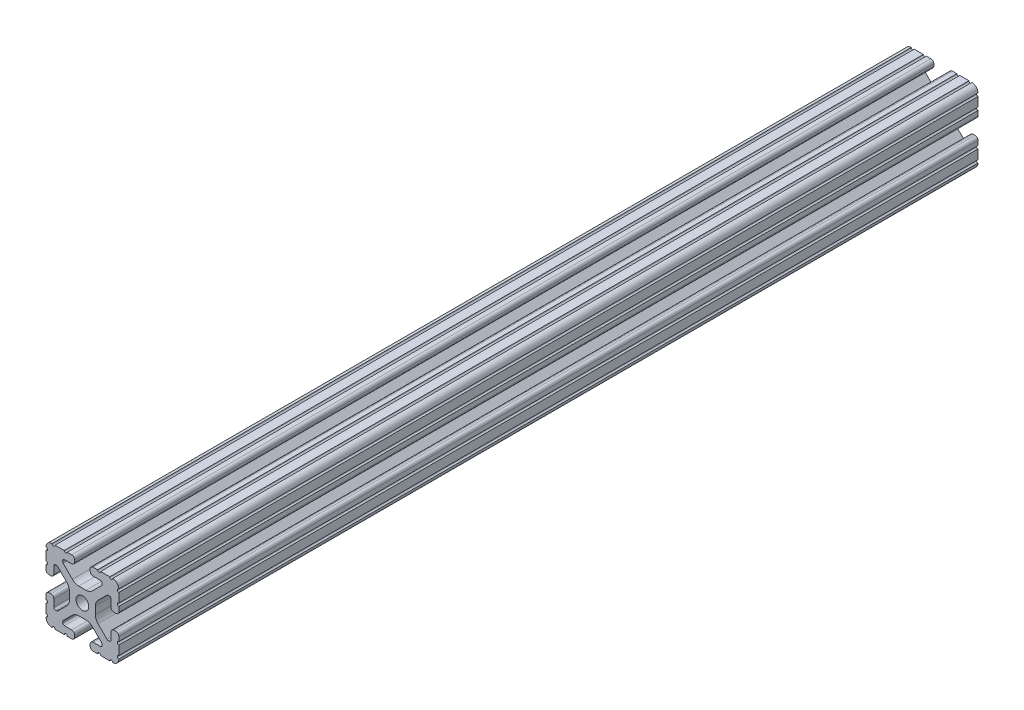
SolidWorks part; units mm, degrees
material "6061 Alloy"
ref_plane "Front Plane" through (0, 0, 0) normal (0, 0, 1) x (1, 0, 0)
ref_plane "Top Plane" through (0, 0, 0) normal (0, 1, 0) x (1, 0, 0)
ref_plane "Right Plane" through (0, 0, 0) normal (1, 0, 0) x (0, 0, -1)
sketch "Sketch1" plane through (0, 0, 0) normal (0, 0, 1) x (1, 0, 0)
  line L0 (0, 25.6181) -> (0, -24.623) construction
  line L1 (-20.8943, 0) -> (20.4607, 0) construction
  line L2 (-10.0229, 12.9148) -> (-5.2522, 8.144)
  line L3 (-10.287, 14.0843) -> (-10.287, 13.5524)
  line L4 (-5.6176, 14.986) -> (-9.3853, 14.986)
  line L5 (-4.064, 17.4964) -> (-4.064, 16.5396)
  line L6 (-7.9742, 19.05) -> (-5.6176, 19.05)
  line L7 (-14.3277, 19.05) -> (-9.4982, 19.05)
  line L8 (-19.05, 9.4961) -> (-19.05, 14.3277)
  line L9 (-19.05, 5.6176) -> (-19.05, 7.9763)
  line L10 (-16.5396, 4.064) -> (-17.4964, 4.064)
  line L11 (-14.986, 9.3853) -> (-14.986, 5.6176)
  line L12 (-13.516, 10.287) -> (-14.0843, 10.287)
  line L13 (-8.1476, 5.2921) -> (-12.8784, 10.0229)
  line L14 (-6.7564, -1.9335) -> (-6.7564, 1.9335)
  line L15 (-12.8784, -10.0229) -> (-8.1476, -5.2921)
  line L16 (-14.0843, -10.287) -> (-13.516, -10.287)
  line L17 (-14.986, -5.6176) -> (-14.986, -9.3853)
  line L18 (-17.4964, -4.064) -> (-16.5396, -4.064)
  line L19 (-19.05, -7.9763) -> (-19.05, -5.6176)
  line L20 (-19.05, -14.3277) -> (-19.05, -9.4961)
  line L21 (-9.4961, -19.05) -> (-14.3277, -19.05)
  line L22 (-5.6176, -19.05) -> (-7.9763, -19.05)
  line L23 (-4.064, -17.4964) -> (-4.064, -16.5396)
  line L24 (10.0229, -12.9148) -> (5.2522, -8.144)
  line L25 (10.287, -14.0843) -> (10.287, -13.5524)
  line L26 (5.6176, -14.986) -> (9.3853, -14.986)
  line L28 (-1.9022, 6.7564) -> (1.9022, 6.7564)
  line L29 (-1.9022, -6.7564) -> (1.9022, -6.7564)
  line L31 (-5.6176, -14.986) -> (-9.3853, -14.986)
  line L32 (-10.287, -14.0843) -> (-10.287, -13.5524)
  line L33 (-10.0229, -12.9148) -> (-5.2522, -8.144)
  line L66 (4.064, -16.5396) -> (4.064, -17.4964)
  line L67 (5.6176, -19.05) -> (7.9763, -19.05)
  line L68 (9.4961, -19.05) -> (14.3277, -19.05)
  line L69 (19.05, -14.3277) -> (19.05, -9.4961)
  line L70 (19.05, -7.9763) -> (19.05, -5.6176)
  line L71 (17.4964, -4.064) -> (16.5396, -4.064)
  line L72 (14.986, -5.6176) -> (14.986, -9.3853)
  line L73 (14.0843, -10.287) -> (13.516, -10.287)
  line L74 (12.8784, -10.0229) -> (8.1476, -5.2921)
  line L75 (6.7564, -1.9335) -> (6.7564, 1.9335)
  line L76 (8.1476, 5.2921) -> (12.8784, 10.0229)
  line L77 (13.516, 10.287) -> (14.0843, 10.287)
  line L78 (14.986, 9.3853) -> (14.986, 5.6176)
  line L79 (16.5396, 4.064) -> (17.4964, 4.064)
  line L80 (19.05, 5.6176) -> (19.05, 7.9763)
  line L81 (19.05, 9.4961) -> (19.05, 14.3277)
  line L82 (14.3277, 19.05) -> (9.4982, 19.05)
  line L83 (7.9742, 19.05) -> (5.6176, 19.05)
  line L84 (4.064, 17.4964) -> (4.064, 16.5396)
  line L85 (5.6176, 14.986) -> (9.3853, 14.986)
  line L86 (10.287, 14.0843) -> (10.287, 13.5524)
  line L87 (10.0229, 12.9148) -> (5.2522, 8.144)
  arc A0 (-10.0229, 12.9148) -> (-10.287, 13.5524) centre (-9.3853, 13.5524) cw
  circle A1 centre (0, 0) radius 3.3274
  arc A2 (-10.287, 14.0843) -> (-9.3853, 14.986) centre (-9.3853, 14.0843) cw
  arc A3 (-4.064, 16.5396) -> (-5.6176, 14.986) centre (-5.6176, 16.5396) cw
  arc A4 (-5.6176, 19.05) -> (-4.064, 17.4964) centre (-5.6176, 17.4964) cw
  arc A5 (-7.9742, 19.05) -> (-9.4982, 19.05) centre (-8.7362, 19.05) cw
  arc A6 (-14.3277, 19.05) -> (-15.8475, 19.05) centre (-15.0876, 18.9933) cw
  arc A7 (-19.05, 15.8475) -> (-15.8475, 19.05) centre (-15.8751, 15.8751) cw
  arc A8 (-19.05, 15.8475) -> (-19.05, 14.3277) centre (-18.9933, 15.0876) cw
  arc A9 (-19.05, 9.4961) -> (-19.05, 7.9763) centre (-18.9933, 8.7362) cw
  arc A10 (-17.4964, 4.064) -> (-19.05, 5.6176) centre (-17.4964, 5.6176) cw
  arc A11 (-14.986, 5.6176) -> (-16.5396, 4.064) centre (-16.5396, 5.6176) cw
  arc A12 (-14.986, 9.3853) -> (-14.0843, 10.287) centre (-14.0843, 9.3853) cw
  arc A13 (-13.516, 10.287) -> (-12.8784, 10.0229) centre (-13.516, 9.3853) cw
  arc A14 (-8.1476, 5.2921) -> (-6.7564, 1.9335) centre (-11.5062, 1.9335) cw
  arc A15 (-6.7564, -1.9335) -> (-8.1476, -5.2921) centre (-11.5062, -1.9335) cw
  arc A16 (-12.8784, -10.0229) -> (-13.516, -10.287) centre (-13.516, -9.3853) cw
  arc A17 (-14.0843, -10.287) -> (-14.986, -9.3853) centre (-14.0843, -9.3853) cw
  arc A18 (-16.5396, -4.064) -> (-14.986, -5.6176) centre (-16.5396, -5.6176) cw
  arc A19 (-19.05, -5.6176) -> (-17.4964, -4.064) centre (-17.4964, -5.6176) cw
  arc A20 (-19.05, -7.9763) -> (-19.05, -9.4961) centre (-18.9933, -8.7362) cw
  arc A21 (-19.05, -14.3277) -> (-19.05, -15.8475) centre (-18.9933, -15.0876) cw
  arc A22 (-15.8475, -19.05) -> (-19.05, -15.8475) centre (-15.8751, -15.8751) cw
  arc A23 (-15.8475, -19.05) -> (-14.3277, -19.05) centre (-15.0876, -18.9933) cw
  arc A24 (-9.4961, -19.05) -> (-7.9763, -19.05) centre (-8.7362, -18.9933) cw
  arc A25 (-4.064, -17.4964) -> (-5.6176, -19.05) centre (-5.6176, -17.4964) cw
  arc A26 (-5.2522, -8.144) -> (-1.9022, -6.7564) centre (-1.9022, -11.494) cw
  arc A27 (1.9022, -6.7564) -> (5.2522, -8.144) centre (1.9022, -11.494) cw
  arc A28 (10.0229, -12.9148) -> (10.287, -13.5524) centre (9.3853, -13.5524) cw
  arc A29 (10.287, -14.0843) -> (9.3853, -14.986) centre (9.3853, -14.0843) cw
  arc A30 (4.064, -16.5396) -> (5.6176, -14.986) centre (5.6176, -16.5396) cw
  arc A31 (-4.064, -16.5396) -> (-5.6176, -14.986) centre (-5.6176, -16.5396) ccw
  arc A32 (-10.287, -14.0843) -> (-9.3853, -14.986) centre (-9.3853, -14.0843) ccw
  arc A33 (-10.0229, -12.9148) -> (-10.287, -13.5524) centre (-9.3853, -13.5524) ccw
  arc A79 (4.064, -17.4964) -> (5.6176, -19.05) centre (5.6176, -17.4964) ccw
  arc A80 (9.4961, -19.05) -> (7.9763, -19.05) centre (8.7362, -18.9933) ccw
  arc A81 (15.8475, -19.05) -> (14.3277, -19.05) centre (15.0876, -18.9933) ccw
  arc A82 (15.8475, -19.05) -> (19.05, -15.8475) centre (15.8751, -15.8751) ccw
  arc A83 (19.05, -14.3277) -> (19.05, -15.8475) centre (18.9933, -15.0876) ccw
  arc A84 (19.05, -7.9763) -> (19.05, -9.4961) centre (18.9933, -8.7362) ccw
  arc A85 (19.05, -5.6176) -> (17.4964, -4.064) centre (17.4964, -5.6176) ccw
  arc A86 (16.5396, -4.064) -> (14.986, -5.6176) centre (16.5396, -5.6176) ccw
  arc A87 (14.0843, -10.287) -> (14.986, -9.3853) centre (14.0843, -9.3853) ccw
  arc A88 (12.8784, -10.0229) -> (13.516, -10.287) centre (13.516, -9.3853) ccw
  arc A89 (6.7564, -1.9335) -> (8.1476, -5.2921) centre (11.5062, -1.9335) ccw
  arc A90 (8.1476, 5.2921) -> (6.7564, 1.9335) centre (11.5062, 1.9335) ccw
  arc A91 (13.516, 10.287) -> (12.8784, 10.0229) centre (13.516, 9.3853) ccw
  arc A92 (14.986, 9.3853) -> (14.0843, 10.287) centre (14.0843, 9.3853) ccw
  arc A93 (14.986, 5.6176) -> (16.5396, 4.064) centre (16.5396, 5.6176) ccw
  arc A94 (17.4964, 4.064) -> (19.05, 5.6176) centre (17.4964, 5.6176) ccw
  arc A95 (19.05, 9.4961) -> (19.05, 7.9763) centre (18.9933, 8.7362) ccw
  arc A96 (19.05, 15.8475) -> (19.05, 14.3277) centre (18.9933, 15.0876) ccw
  arc A97 (19.05, 15.8475) -> (15.8475, 19.05) centre (15.8751, 15.8751) ccw
  arc A98 (14.3277, 19.05) -> (15.8475, 19.05) centre (15.0876, 18.9933) ccw
  arc A99 (7.9742, 19.05) -> (9.4982, 19.05) centre (8.7362, 19.05) ccw
  arc A100 (5.6176, 19.05) -> (4.064, 17.4964) centre (5.6176, 17.4964) ccw
  arc A101 (4.064, 16.5396) -> (5.6176, 14.986) centre (5.6176, 16.5396) ccw
  arc A102 (10.287, 14.0843) -> (9.3853, 14.986) centre (9.3853, 14.0843) ccw
  arc A103 (10.0229, 12.9148) -> (10.287, 13.5524) centre (9.3853, 13.5524) ccw
  arc A104 (1.9022, 6.7564) -> (5.2522, 8.144) centre (1.9022, 11.494) ccw
  arc A105 (-5.2522, 8.144) -> (-1.9022, 6.7564) centre (-1.9022, 11.494) ccw
  dimension "D1" = 6.6548
  dimension "D2" = 19.05
  dimension "D3" = 38.1
  dimension "D4" = 20.574
  dimension "D5" = 13.5128
  dimension "D6" = 4.064
  dimension "D7" = 8.128
  dimension "D8" = 4.064
  dimension "D9" = 12.2936
extrude "Extrude1" add sketch "Sketch1" against normal blind 449.58
